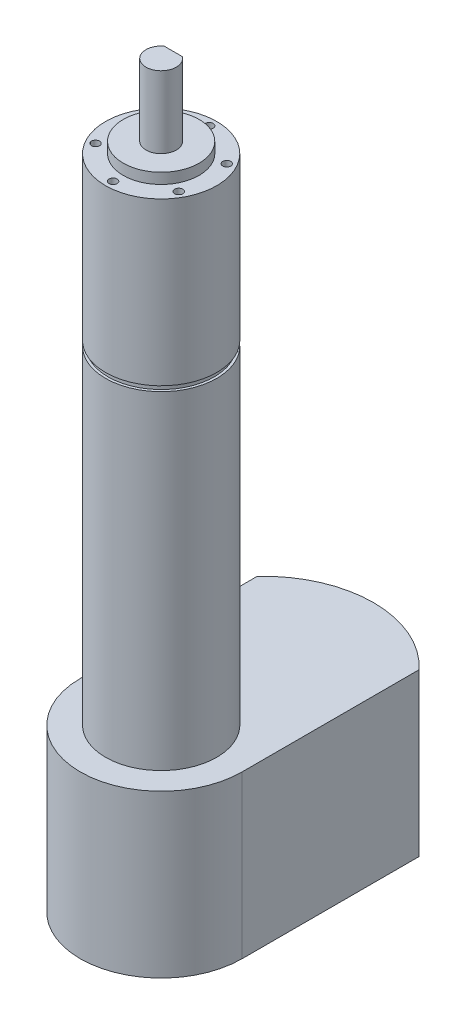
SolidWorks part; units mm, degrees
ref_plane "前视基准面" through (0, 0, 0) normal (0, 0, 1) x (1, 0, 0)
ref_plane "上视基准面" through (0, 0, 0) normal (0, 1, 0) x (1, 0, 0)
ref_plane "右视基准面" through (0, 0, 0) normal (1, 0, 0) x (0, 0, -1)
sketch "草图1" plane through (0, 0, 0) normal (0, 0, 1) x (1, 0, 0)
  line L0 (0, 60.6507) -> (0, -47.8106) construction
  line L1 (-65.0072, 0) -> (54.4247, 0) construction
  line L2 (0, 0) -> (11, 0)
  line L3 (11, 0) -> (11, 64.9)
  line L4 (11, 64.9) -> (10.5, 64.9)
  line L5 (10.5, 64.9) -> (10.5, 65.9)
  line L6 (10.5, 65.9) -> (11, 65.9)
  line L7 (11, 65.9) -> (11, 97.9)
  line L8 (11, 97.9) -> (7.5, 97.9)
  line L9 (7.5, 97.9) -> (7.5, 100)
  line L10 (7.5, 100) -> (3, 100)
  line L11 (3, 100) -> (3, 114.2)
  line L12 (3, 114.2) -> (0, 114.2)
  line L13 (0, 114.2) -> (0, 0)
  dimension "D1" = 22
  dimension "D2" = 1
  dimension "D3" = 0.5
  dimension "D4" = 6
  dimension "D5" = 15
  dimension "D6" = 2.1
  dimension "D7" = 16.3
  dimension "D8" = 100
  dimension "D9" = 32
revolve "旋转1" add sketch "草图1" angle 360 about L0
sketch "草图2" plane through (0, 114.2, 0) normal (0, 1, 0) x (1, 0, 0)
  line L0 (-1.8, 2.4) -> (1.8, 2.4)
  circle A1 centre (0, 0) radius 3
  circle A2 centre (0, 0) radius 3
  point P5 (0, -3)
  circle M2 centre (0, 0) radius 3
  dimension "D2" = 5.4
  dimension "D1" = 0
extrude "切除-拉伸1" cut sketch "草图2" against normal blind 10.2 contours L0 M2
sketch "草图3" plane through (0, 0, 0) normal (0, -1, 0) x (1, 0, 0)
  line L0 (-16, 0) -> (-16, -35)
  line L1 (0, 43.4341) -> (0, -58.7129) construction
  line L2 (16, 0) -> (16, -35)
  arc A0 (16, 0) -> (-16, 0) centre (0, 0) ccw
  arc A1 (-16, -35) -> (16, -35) centre (0, -20.2143) ccw
  point P10 (0, -42)
  dimension "D1" = 32
  dimension "D2" = 35
  dimension "D3" = 42
extrude "凸台-拉伸1" add sketch "草图3" along normal blind 32
sketch "草图4" plane through (0, 97.9, 0) normal (0, 1, 0) x (1, 0, 0)
  circle A0 centre (0, 0) radius 9.5 construction
  point P3 (0, 9.5)
  point P4 (8.2272, 4.75)
  point P7 (8.2272, -4.75)
  point P8 (0, -9.5)
  point P9 (-8.2272, -4.75)
  point P10 (-8.2272, 4.75)
  point P11 (0, 0)
  dimension "D1" = 19
  dimension "D2" = 6
hole_wizard "M2 螺纹孔1" positions "草图5" profile "草图6" tap size "M2" standard "GB"
sketch "草图5" plane through (0, 97.9, 0) normal (0, 1, 0) x (1, 0, 0)
  point P0 (0, 9.5)
  point P3 (-8.2272, 4.75)
  point P6 (-8.2272, -4.75)
  point P9 (0, -9.5)
  point P12 (8.2272, -4.75)
  point P15 (8.2272, 4.75)
sketch "草图6" plane through (0, 97.9, -9.5) normal (1, 0, 0) x (0, 0, 1)
  line L0 (0, 0) -> (0, 5.4807)
  line L1 (0, 5.4807) -> (0.8, 5)
  line L2 (0.8, 5) -> (0.8, 0)
  line L5 (0.8, 0) -> (0, 0)
  line L10 (0, 5.4807) -> (-0.8, 5) construction
  line L11 (0, -6.35) -> (0, 107.95) construction
  dimension "螺纹孔钻头直径" = 1.6
  dimension "螺纹孔钻头深度" = 5
  dimension "导头角度" = 118
cosmetic thread "孔螺蚊线1" parameters "D1"=3, "D2"=2
cosmetic thread "孔螺蚊线2" parameters "D1"=3, "D2"=2
cosmetic thread "孔螺蚊线3" parameters "D1"=3, "D2"=2
cosmetic thread "孔螺蚊线4" parameters "D1"=3, "D2"=2
cosmetic thread "孔螺蚊线5" parameters "D1"=3, "D2"=2
cosmetic thread "孔螺蚊线6" parameters "D1"=3, "D2"=2
move or copy body "实体-移动/复制1" [suppressed] bodies to move or copy 109
